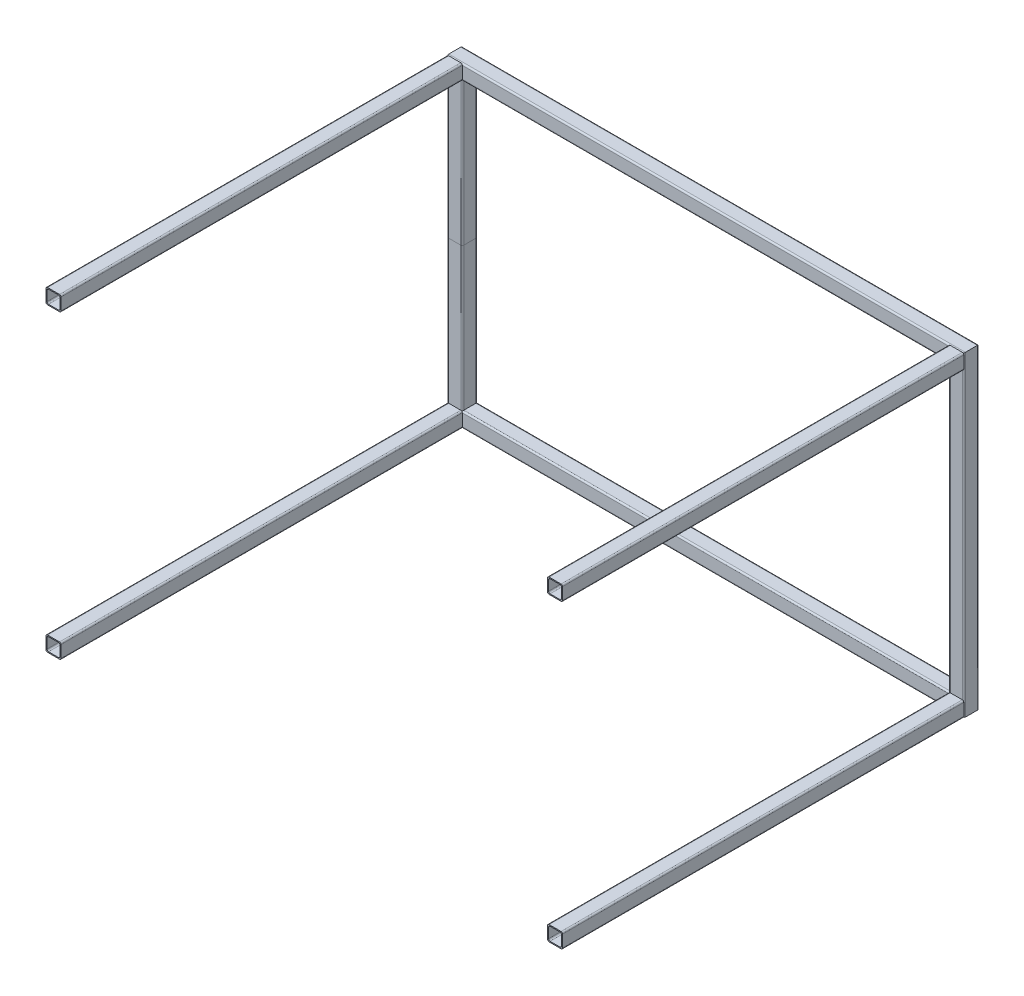
SolidWorks part; units mm, degrees
ref_plane "Plan de face" through (0, 0, 0) normal (0, 0, 1) x (1, 0, 0)
ref_plane "Plan de dessus" through (0, 0, 0) normal (0, 1, 0) x (1, 0, 0)
ref_plane "Plan de droite" through (0, 0, 0) normal (1, 0, 0) x (0, 0, -1)
sketch "Esquisse1" plane through (0, 0, 0) normal (0, 0, 1) x (1, 0, 0)
  line L1 (-600, -400) -> (600, -400)
  line L2 (-600, -400) -> (-600, 400)
  line L3 (-600, 400) -> (600, 400)
  line L4 (600, -400) -> (600, 400)
  line L5 (-600, -400) -> (600, 400) construction
  line L6 (-600, 400) -> (600, -400) construction
  point P0 (0, 0)
  dimension "D1" = 1200
  dimension "D2" = 800
sketch "Esquisse2" plane through (0, 0, 0) normal (0, 1, 0) x (1, 0, 0)
  line L0 (-600, 0) -> (600, 0) construction
  line L1 (-512, -15) -> (-488, -15)
  line L2 (-515, -12) -> (-515, 12)
  line L3 (-512, 15) -> (-488, 15)
  line L4 (-485, -12) -> (-485, 12)
  line L5 (-515, -15) -> (-485, 15) construction
  line L6 (-515, 15) -> (-485, -15) construction
  line L7 (-600, 0) -> (600, 0) construction
  line L9 (-510, -13) -> (-490, -13)
  line L10 (-513, -10) -> (-513, 10)
  line L11 (-510, 13) -> (-490, 13)
  line L12 (-487, -10) -> (-487, 10)
  line L13 (-513, -13) -> (-487, 13) construction
  line L14 (-513, 13) -> (-487, -13) construction
  arc A0 (-490, -13) -> (-487, -10) centre (-490, -10) ccw
  arc A1 (-513, 10) -> (-510, 13) centre (-510, 10) cw
  arc A2 (-510, -13) -> (-513, -10) centre (-510, -10) cw
  arc A3 (-490, 13) -> (-487, 10) centre (-490, 10) cw
  arc A4 (-488, -15) -> (-485, -12) centre (-488, -12) ccw
  arc A5 (-512, -15) -> (-515, -12) centre (-512, -12) cw
  arc A6 (-488, 15) -> (-485, 12) centre (-488, 12) cw
  arc A7 (-515, 12) -> (-512, 15) centre (-512, 12) cw
  point P0 (-500, 0)
  point P9 (-500, 0)
  dimension "D5" = 3
  dimension "D1" = 30
  dimension "D2" = 30
  dimension "D3" = 26
  dimension "D4" = 26
sweep "Balayage1" add profiles "Esquisse2" path "Esquisse1"
sketch "Esquisse3" plane through (0, 0, 15) normal (0, 0, 1) x (1, 0, 0)
  line L1 (-512, 285) -> (-488, 285)
  line L2 (-515, 288) -> (-515, 312)
  line L3 (-512, 315) -> (-488, 315)
  line L4 (-485, 288) -> (-485, 312)
  line L5 (-500, 315) -> (-500, 285) construction
  line L6 (-515, 300) -> (-485, 300) construction
  line L7 (-488, 288) -> (-512, 312) construction
  line L8 (-510, 287) -> (-490, 287)
  line L9 (-513, 290) -> (-513, 310)
  line L10 (-510, 313) -> (-490, 313)
  line L11 (-487, 290) -> (-487, 310)
  line L12 (-500, 313) -> (-500, 287) construction
  line L13 (-513, 300) -> (-487, 300) construction
  line L14 (0, 354.9683) -> (0, -415.7461) construction
  line L15 (-462.9458, 0) -> (284.4919, 0) construction
  line L16 (513, 300) -> (487, 300) construction
  line L17 (500, 313) -> (500, 287) construction
  line L18 (515, 300) -> (485, 300) construction
  line L19 (500, 315) -> (500, 285) construction
  line L20 (487, 290) -> (487, 310)
  line L21 (510, 313) -> (490, 313)
  line L22 (513, 290) -> (513, 310)
  line L23 (510, 287) -> (490, 287)
  line L24 (485, 288) -> (485, 312)
  line L25 (512, 315) -> (488, 315)
  line L26 (515, 288) -> (515, 312)
  line L27 (512, 285) -> (488, 285)
  line L28 (-512, -315) -> (-488, -315)
  line L29 (-485, -288) -> (-485, -312)
  line L30 (-512, -285) -> (-488, -285)
  line L31 (-510, -287) -> (-490, -287)
  line L32 (-510, -313) -> (-490, -313)
  line L33 (-487, -290) -> (-487, -310)
  line L34 (-513, -290) -> (-513, -310)
  line L35 (-515, -288) -> (-515, -312)
  line L36 (500, -315) -> (500, -285) construction
  line L37 (515, -300) -> (485, -300) construction
  line L38 (500, -313) -> (500, -287) construction
  line L39 (513, -300) -> (487, -300) construction
  line L40 (512, -285) -> (488, -285)
  line L41 (515, -288) -> (515, -312)
  line L42 (512, -315) -> (488, -315)
  line L43 (485, -288) -> (485, -312)
  line L44 (510, -287) -> (490, -287)
  line L45 (513, -290) -> (513, -310)
  line L46 (510, -313) -> (490, -313)
  line L47 (487, -290) -> (487, -310)
  arc A0 (-510, 287) -> (-513, 290) centre (-510, 290) cw
  arc A1 (-512, 285) -> (-515, 288) centre (-512, 288) cw
  arc A2 (-488, 285) -> (-485, 288) centre (-488, 288) ccw
  arc A3 (-490, 287) -> (-487, 290) centre (-490, 290) ccw
  arc A4 (-513, 310) -> (-510, 313) centre (-510, 310) cw
  arc A5 (-490, 313) -> (-487, 310) centre (-490, 310) cw
  arc A6 (-488, 315) -> (-485, 312) centre (-488, 312) cw
  arc A7 (-515, 312) -> (-512, 315) centre (-512, 312) cw
  arc A8 (515, 312) -> (512, 315) centre (512, 312) ccw
  arc A9 (488, 315) -> (485, 312) centre (488, 312) ccw
  arc A10 (490, 313) -> (487, 310) centre (490, 310) ccw
  arc A11 (513, 310) -> (510, 313) centre (510, 310) ccw
  arc A12 (490, 287) -> (487, 290) centre (490, 290) cw
  arc A13 (488, 285) -> (485, 288) centre (488, 288) cw
  arc A14 (512, 285) -> (515, 288) centre (512, 288) ccw
  arc A15 (510, 287) -> (513, 290) centre (510, 290) ccw
  arc A16 (-488, -315) -> (-485, -312) centre (-488, -312) ccw
  arc A17 (-488, -285) -> (-485, -288) centre (-488, -288) cw
  arc A18 (-490, -287) -> (-487, -290) centre (-490, -290) cw
  arc A19 (-490, -313) -> (-487, -310) centre (-490, -310) ccw
  arc A20 (-513, -310) -> (-510, -313) centre (-510, -310) ccw
  arc A21 (-510, -287) -> (-513, -290) centre (-510, -290) ccw
  arc A22 (-515, -312) -> (-512, -315) centre (-512, -312) ccw
  arc A23 (-512, -285) -> (-515, -288) centre (-512, -288) ccw
  arc A24 (510, -287) -> (513, -290) centre (510, -290) cw
  arc A25 (512, -285) -> (515, -288) centre (512, -288) cw
  arc A26 (488, -285) -> (485, -288) centre (488, -288) ccw
  arc A27 (490, -287) -> (487, -290) centre (490, -290) ccw
  arc A28 (513, -310) -> (510, -313) centre (510, -310) cw
  arc A29 (490, -313) -> (487, -310) centre (490, -310) cw
  arc A30 (488, -315) -> (485, -312) centre (488, -312) cw
  arc A31 (515, -312) -> (512, -315) centre (512, -312) cw
  point P0 (-500, 300)
  point P7 (-500, 300)
  point P17 (-513, 287)
  point P23 (-515, 285)
  point P28 (-487, 287)
  point P31 (-513, 313)
  point P36 (-485, 315)
  point P39 (-515, 315)
  point P76 (515, 315)
  point P77 (485, 315)
  point P78 (513, 313)
  point P79 (487, 287)
  point P80 (515, 285)
  point P81 (513, 287)
  point P82 (500, 300)
  point P107 (-515, -315)
  point P108 (-513, -313)
  point P109 (-515, -285)
  point P110 (-513, -287)
  point P146 (500, -300)
  point P147 (513, -287)
  point P148 (515, -285)
  point P149 (487, -287)
  point P150 (513, -313)
  point P151 (485, -315)
  point P152 (515, -315)
  dimension "D5" = 3
  dimension "D1" = 30
  dimension "D2" = 30
  dimension "D3" = 26
  dimension "D4" = 26
extrude "Boss.-Extru.1" add sketch "Esquisse3" along normal blind 800
